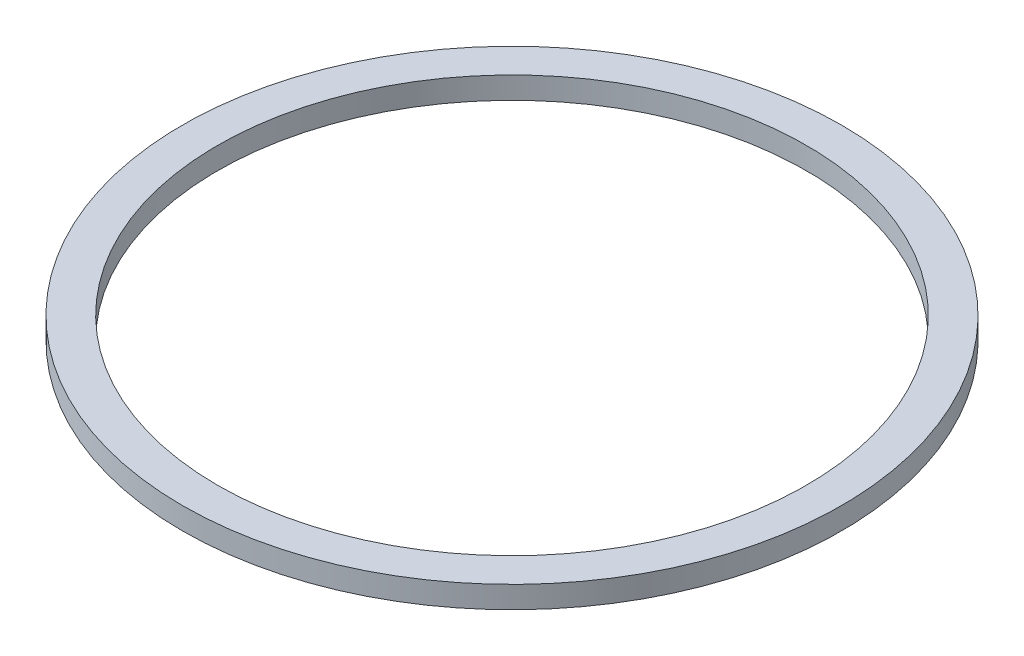
SolidWorks part; units mm, degrees
ref_plane "Front Plane" through (0, 0, 0) normal (0, 0, 1) x (1, 0, 0)
ref_plane "Top Plane" through (0, 0, 0) normal (0, 1, 0) x (1, 0, 0)
ref_plane "Right Plane" through (0, 0, 0) normal (1, 0, 0) x (0, 0, -1)
sketch "Sketch1" plane through (0, 0, 0) normal (0, 1, 0) x (1, 0, 0)
  circle A0 centre (0, 0) radius 34.036
  circle A1 centre (0, 0) radius 38.1
  dimension "D1" = 76.2
  dimension "D2" = 4.064
extrude "Boss-Extrude1" add sketch "Sketch1" along normal blind 2.54
